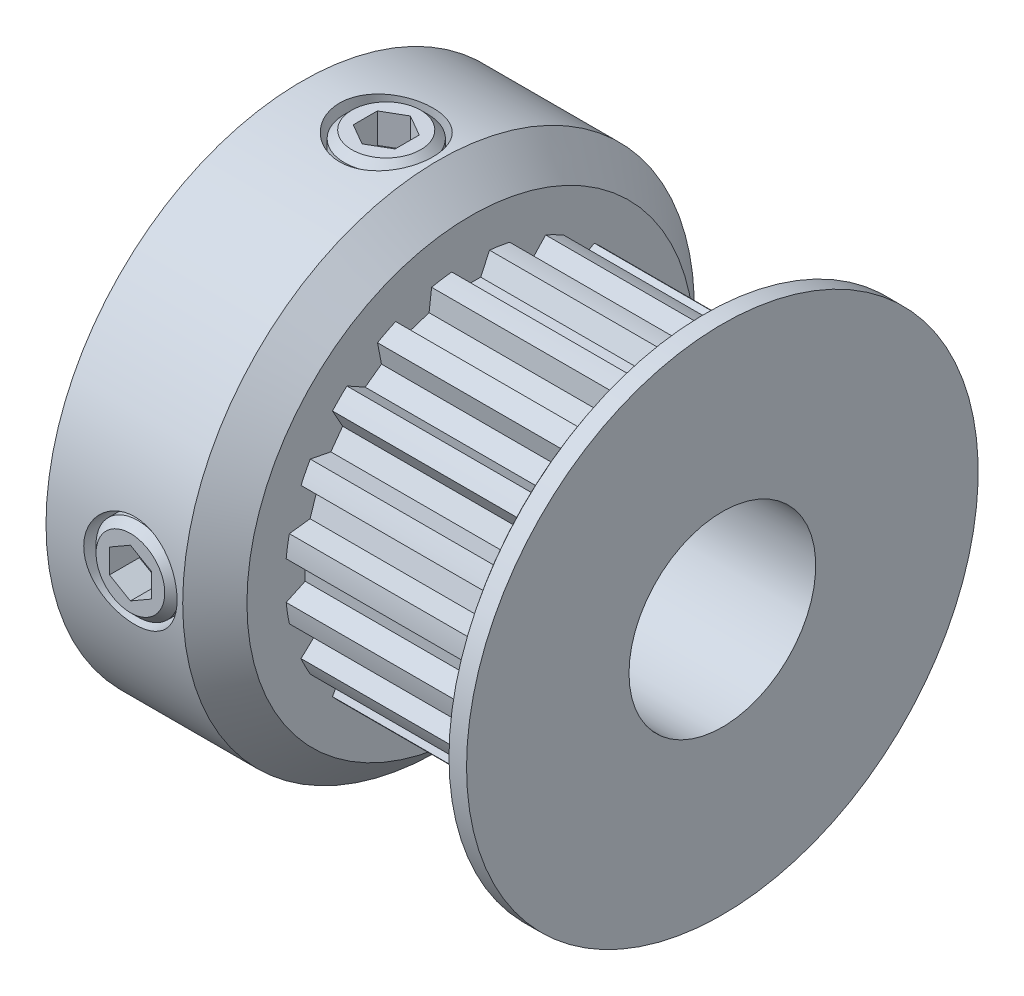
SolidWorks part; units mm, degrees
ref_plane "Front Plane" through (0, 0, 0) normal (0, 0, 1) x (1, 0, 0)
ref_plane "Top Plane" through (0, 0, 0) normal (0, 1, 0) x (1, 0, 0)
ref_plane "Right Plane" through (0, 0, 0) normal (1, 0, 0) x (0, 0, -1)
sketch "Sketch2" plane through (0, 0, 0) normal (1, 0, 0) x (0, 0, -1)
  line L3 (0, 0) -> (0, 5.6388) construction
  line L6 (0, -6.1468) -> (0, -6.4643) construction
  line L7 (-0.5715, 6.1202) -> (-0.3422, 5.6284)
  line L8 (0.5715, 6.1202) -> (0.3422, 5.6284)
  line L9 (-0.5715, 6.1202) -> (-0.6426, 6.2727)
  line L10 (0.5715, 6.1202) -> (0.6426, 6.2727)
  line L12 (-0.3422, 5.6284) -> (0.3422, 5.6284)
  line L14 (0, 6.1468) -> (0, 6.4643) construction
  line L15 (0, 0) -> (0, -1.143) construction
  circle A0 centre (0, 0) radius 6.4643 construction
  circle A1 centre (0, 0) radius 5.6388 construction
  circle A2 centre (0, 0) radius 6.1468 construction
  arc A7 (0.6426, 6.2727) -> (-0.6426, 6.2727) centre (0, 0) ccw
  point P5 (0, 6.3056)
  dimension "D3" = 0.3175
  dimension "D1" = 50
sketch "Sketch1" plane through (0, 0, 0) normal (0, 0, 1) x (1, 0, 0)
  line L0 (-7.1501, 0) -> (7.1501, 0) construction
  line L1 (-7.1501, 3.175) -> (7.1501, 3.175)
  line L2 (-7.1501, 3.175) -> (-7.1501, 8.6995)
  line L3 (-7.1501, 8.6995) -> (-2.5019, 8.6995)
  line L4 (-2.5019, 8.6995) -> (-1.4097, 7.6073)
  line L5 (-1.4097, 7.6073) -> (-1.4097, 6.4643)
  line L6 (-1.4097, 6.4643) -> (5.9563, 6.4643)
  line L7 (5.9563, 6.4643) -> (5.9563, 7.0358)
  line L8 (5.9563, 6.4643) -> (7.1501, 6.4643) construction
  line L9 (6.5532, 8.6995) -> (7.1501, 8.6995)
  line L10 (7.1501, 8.6995) -> (7.1501, 3.175)
  line L11 (6.5532, 6.4643) -> (6.5532, 8.6995) construction
  line L12 (-4.826, 8.6995) -> (-4.826, 3.175) construction
  arc A0 (5.9563, 7.0358) -> (6.5532, 8.6995) centre (8.5733, 7.0358) cw
  dimension "Bore Size" = 6.35
  dimension "Overall Width" = 14.3002
  dimension "Inside Width" = 7.366
  dimension "Outside Width" = 8.5598
  dimension "Hub Dia" = 17.399
  dimension "OD" = 17.399
  dimension "D1" = 45
  dimension "D2" = 12.9286
  dimension "D3" = 1.143
  dimension "D4" = 0.5715
revolve "Revolve1" add sketch "Sketch1" angle 360 mid plane about L0
sketch "Sketch4" plane through (-1.4097, 0, 0) normal (1, 0, 0) x (0, 0, -1)
  circle A0 centre (0, 0) radius 6.3056
  circle A1 centre (0, 0) radius 6.4643 construction
  circle A2 centre (0, 0) radius 6.4643
extrude "Cut-Extrude2" cut sketch "Sketch4" along normal up to surface (7.366 mm away) up to face at (5.9563, 0, 6.4643)
sketch "Sketch3" plane through (-1.4097, 0, 0) normal (1, 0, 0) x (0, 0, -1)
  line L2 (-0.5715, 6.1202) -> (-0.3422, 5.6284) construction
  line L3 (-0.3422, 5.6284) -> (0.3422, 5.6284) construction
  line L4 (0.5715, 6.1202) -> (0.3422, 5.6284) construction
  line L5 (-0.6426, 6.2727) -> (-0.3422, 5.6284)
  line L6 (-0.3422, 5.6284) -> (0.3422, 5.6284)
  line L7 (0.6426, 6.2727) -> (0.3422, 5.6284)
  arc A1 (0.6426, 6.2727) -> (-0.6426, 6.2727) centre (0, 0) ccw construction
  arc A2 (0.6426, 6.2727) -> (-0.6426, 6.2727) centre (0, 0) ccw
extrude "Cut-Extrude1" cut sketch "Sketch3" along normal up to surface (7.366 mm away) up to face at (5.9563, 0, 7.0358)
pattern_circular "CirPattern1" count 20 over 360 about axis through (0, 0, 0) along (1, 0, 0) of "Cut-Extrude1"
sketch "Sketch5" plane through (0, 0, 0) normal (0, 0, 1) x (1, 0, 0)
  line L1 (5.9563, 7.0358) -> (5.9563, -7.0358) construction
  point P0 (5.9563, 0)
sketch "Sketch6" plane through (0, 0, 0) normal (0, 1, 0) x (1, 0, 0)
  line L0 (-7.1501, 0) -> (-5.8674, 0) construction
  line L1 (-7.1501, 8.6995) -> (-7.1501, -8.6995) construction
  line L2 (-1.4097, 0) -> (-2.6924, 0) construction
  line L3 (-1.4097, -0.3422) -> (-1.4097, 0.3422) construction
  circle A0 centre (-4.2799, 0) radius 1.5875
  dimension "D1" = 3.175
extrude "Cut-Extrude3" cut sketch "Sketch6" along normal through all
sketch "Sketch7" plane through (0, 0, 0) normal (0, 0, 1) x (1, 0, 0)
  line L0 (-5.4483, 8.6995) -> (-4.2799, 8.6995)
  line L1 (-5.7023, 8.4455) -> (-5.7023, 3.81)
  line L2 (-5.7023, 3.81) -> (-5.4483, 3.556)
  line L3 (-5.4483, 3.556) -> (-4.2799, 3.556)
  line L4 (-4.2799, 3.556) -> (-4.2799, 8.6995) construction
  line L6 (-5.7023, 8.4455) -> (-5.4483, 8.6995)
  line L7 (-7.1501, 8.6995) -> (-2.5019, 8.6995) construction
  line L8 (-4.2799, 8.6995) -> (-4.2799, 3.556)
  point P0 (-5.7023, 8.6995)
  point P4 (-5.7023, 3.556)
  dimension "D1" = 2.8448
  dimension "D2" = 0.381
revolve "Revolve2" add sketch "Sketch7" angle 360 mid plane about L4
sketch "Sketch8" plane through (0, 8.6995, 0) normal (0, 1, 0) x (1, 0, 0)
  line L1 (-4.2799, 0.8212) -> (-4.9911, 0.4106)
  line L2 (-4.9911, 0.4106) -> (-4.9911, -0.4106)
  line L3 (-4.9911, -0.4106) -> (-4.2799, -0.8212)
  line L4 (-4.2799, -0.8212) -> (-3.5687, -0.4106)
  line L5 (-3.5687, -0.4106) -> (-3.5687, 0.4106)
  line L6 (-3.5687, 0.4106) -> (-4.2799, 0.8212)
  circle A0 centre (-4.2799, 0) radius 0.7112 construction
  dimension "D1" = 1.4224
extrude "Cut-Extrude4" cut sketch "Sketch8" against normal blind 1.016
pattern_circular "CirPattern2" count 2 over 90 about axis through (-7.1501, 0, 0) along (-1, 0, 0) of "Cut-Extrude3"
pattern_circular "CirPattern3" count 2 over 90 about axis through (0, 0, 0) along (1, 0, 0) of bodies 107
equation "\"D3@Sketch2\" = (\"hs@Sketch2\"-\"ht@Sketch2\")/2"
equation "\"D2@Sketch1\" = \"PD@Sketch2\""
equation "\"D3@Sketch1\" = \"hs@Sketch2\""
equation "\"D4@Sketch1\" = \"D3@Sketch1\"/2"
